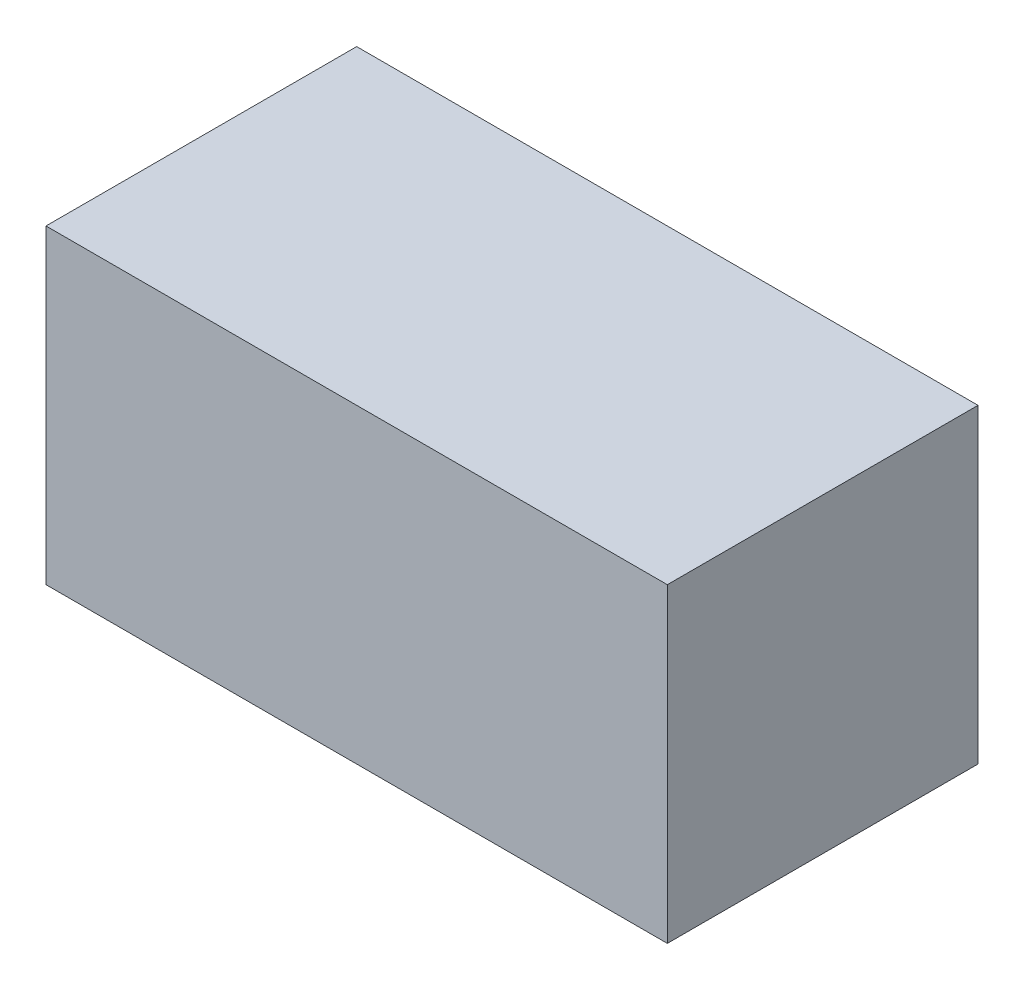
SolidWorks part; units mm, degrees
ref_plane "前视基准面" through (0, 0, 0) normal (0, 0, 1) x (1, 0, 0)
ref_plane "上视基准面" through (0, 0, 0) normal (0, 1, 0) x (1, 0, 0)
ref_plane "右视基准面" through (0, 0, 0) normal (1, 0, 0) x (0, 0, -1)
other "Configuration Table"
sketch "SelectionSeed" plane through (0, 0, 0) normal (0, 0, 1) x (1, 0, 0)
  line L1 (0, 0) -> (10, 0)
  line L2 (0, 0) -> (0, 10)
  line L3 (0, 10) -> (10, 10)
  line L4 (10, 0) -> (10, 10)
  line L6 (20, 0) -> (40, 0)
  line L7 (20, 0) -> (20, 10)
  line L8 (20, 10) -> (40, 10)
  line L9 (40, 0) -> (40, 10)
extrude "SelectionExtrude" add sketch "SelectionSeed" along normal blind 10 contours L6 L9 L8 L7
